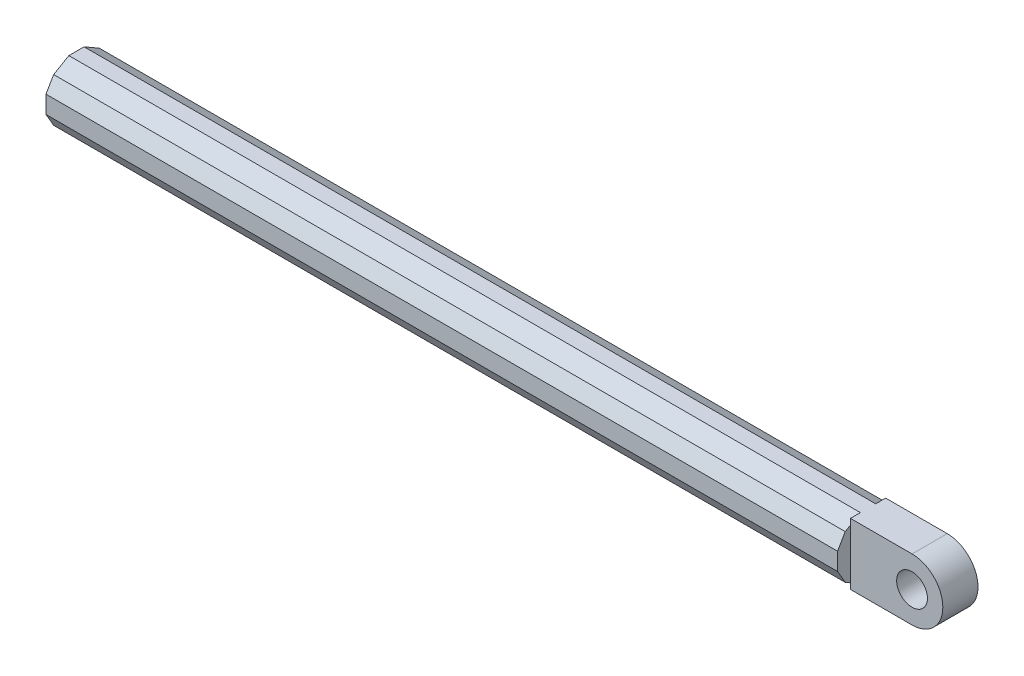
SolidWorks part; units mm, degrees
ref_plane "Front Plane" through (0, 0, 0) normal (0, 0, 1) x (1, 0, 0)
ref_plane "Top Plane" through (0, 0, 0) normal (0, 1, 0) x (1, 0, 0)
ref_plane "Right Plane" through (0, 0, 0) normal (1, 0, 0) x (0, 0, -1)
sketch "Sketch1" plane through (0, 0, 0) normal (1, 0, 0) x (0, 0, -1)
  line L0 (0, 0) -> (3.4641, 0) construction
  line L1 (3.4641, -2) -> (3.4641, 2)
  line L2 (3.4641, 2) -> (0, 4)
  line L3 (0, 4) -> (-3.4641, 2)
  line L4 (-3.4641, 2) -> (-3.4641, -2)
  line L5 (-3.4641, -2) -> (0, -4)
  line L6 (0, -4) -> (3.4641, -2)
  circle A0 centre (0, 0) radius 3.4641 construction
  dimension "D1" = 4
extrude "Boss-Extrude1" add sketch "Sketch1" along normal blind 90
sketch "Sketch5" plane through (0, 0, 0) normal (-1, 0, 0) x (0, 0, 1)
  line L0 (0, 0) -> (2.375, 0) construction
  line L1 (2.375, -1.3712) -> (2.375, 1.3712)
  line L2 (2.375, 1.3712) -> (0, 2.7424)
  line L3 (0, 2.7424) -> (-2.375, 1.3712)
  line L4 (-2.375, 1.3712) -> (-2.375, -1.3712)
  line L5 (-2.375, -1.3712) -> (0, -2.7424)
  line L6 (0, -2.7424) -> (2.375, -1.3712)
  circle A0 centre (0, 0) radius 2.375 construction
  circle A1 centre (1.1875, 2.0568) radius 0.25
  circle A2 centre (2.375, 0) radius 0.25
  circle A3 centre (1.1875, -2.0568) radius 0.25
  circle A4 centre (-1.1875, -2.0568) radius 0.25
  circle A5 centre (-2.375, 0) radius 0.25
  circle A6 centre (-1.1875, 2.0568) radius 0.25
  point P23 (0, 0)
  dimension "D3" = 0.5
  dimension "D1" = 4.75
  dimension "D2" = 6
extrude "Cut-Extrude1" cut sketch "Sketch5" against normal blind 10 contours A6 L3 L4 A5 L5 A4 L6 A3 L1 A2 L2 A1
chamfer "Chamfer1" distance 1 angle 30 6 edges at (45, 2, 3.4641) (45, 4, 0) (45, 2, -3.4641) (45, -2, -3.4641) (45, -2, 3.4641) (45, -4, 0)
sketch "Sketch2" plane through (0, 0, 0) normal (0, 0, 1) x (1, 0, 0)
  line L3 (90, 3.5) -> (97, 3.5)
  line L4 (97, -3.5) -> (90, -3.5)
  line L5 (90, 3.5) -> (90, -3.5)
  arc A2 (97, 3.5) -> (97, -3.5) centre (97, 0) cw
  circle A3 centre (97, 0) radius 1.75
  point P8 (90, 3.5)
  point P9 (90, -3.5)
  dimension "D1" = 3.5
  dimension "D2" = 7
extrude "Boss-Extrude2" add sketch "Sketch2" along normal blind 2 and the other way blind 2
